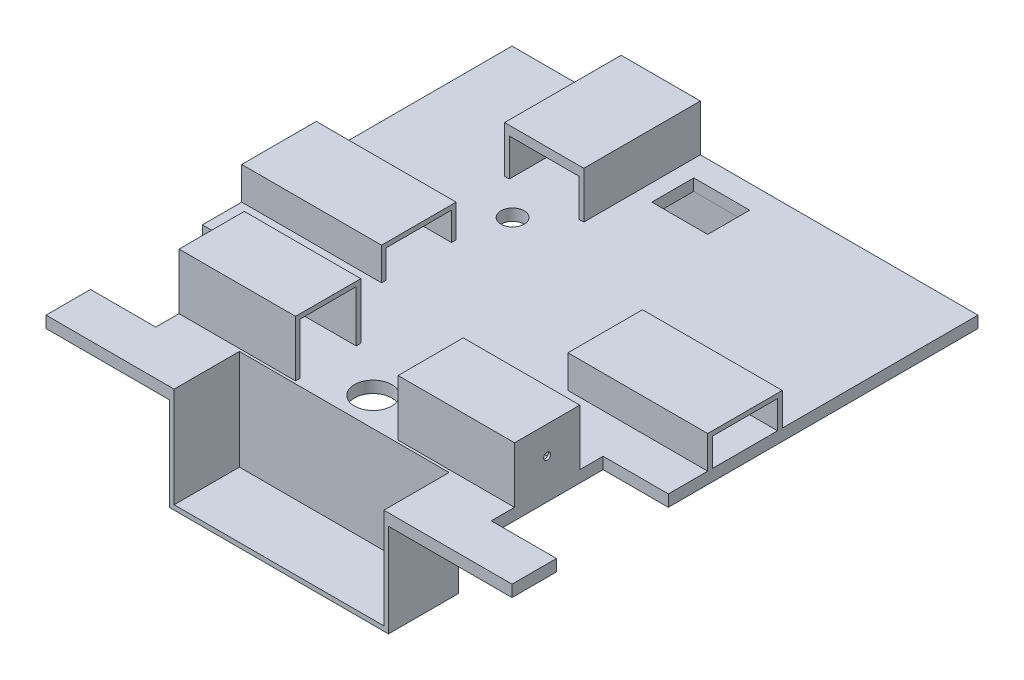
SolidWorks part; units mm, degrees
ref_plane "Front Plane" through (0, 0, 0) normal (0, 0, 1) x (1, 0, 0)
ref_plane "Top Plane" through (0, 0, 0) normal (0, 1, 0) x (1, 0, 0)
ref_plane "Right Plane" through (0, 0, 0) normal (1, 0, 0) x (0, 0, -1)
sketch "Sketch1" plane through (0, 0, 0) normal (0, 1, 0) x (1, 0, 0)
  line L0 (-50, -50) -> (-50, 50)
  line L1 (-50, -50) -> (50, -50)
  line L2 (-50, 50) -> (50, 50)
  line L3 (50, -50) -> (50, 50)
  line L4 (50, -16.4531) -> (36, -16.4531)
  line L5 (36, -16.4531) -> (36, -40.4531)
  line L6 (36, -40.4531) -> (50, -40.4531)
  line L7 (-36, -40.4531) -> (-50, -40.4531)
  line L8 (-36, -16.4531) -> (-36, -40.4531)
  line L9 (-50, -16.4531) -> (-36, -16.4531)
  line L10 (-6, 45) -> (6, 45)
  line L11 (-6, 45) -> (-6, 36)
  line L12 (6, 45) -> (6, 36)
  line L13 (-6, 36) -> (6, 36)
  dimension "D1" = 14
  dimension "D2" = 24
  dimension "D3" = 9
  dimension "D4" = 12
extrude "Boss-Extrude1" add sketch "Sketch1" along normal blind 2.5 contours L0 L9 L8 L7 L1 L3 L6 L5 L4 L2 L13 L11 L10 L12
sketch "Sketch2" plane through (0, 2.5, 0) normal (0, 1, 0) x (1, 0, 0)
  line L0 (-26.5835, 50) -> (-9.5835, 50)
  line L1 (-26.5835, 50) -> (-26.5835, 25)
  line L2 (-9.5835, 50) -> (-9.5835, 25)
  line L3 (-26.5835, 25) -> (-9.5835, 25)
  line L4 (-50, 50) -> (50, 50) construction
  dimension "D1" = 17
  dimension "D2" = 25
extrude "Boss-Extrude2" add sketch "Sketch2" along normal blind 10
sketch "Sketch4" plane through (0, 0, -25) normal (0, 0, 1) x (1, 0, 0)
  line L0 (-25.5835, 2.5) -> (-10.5835, 2.5)
  line L1 (-25.5835, 2.5) -> (-25.5835, 10.5)
  line L2 (-10.5835, 2.5) -> (-10.5835, 10.5)
  line L3 (-25.5835, 10.5) -> (-10.5835, 10.5)
  line L5 (-26.5835, 2.5) -> (-9.5835, 2.5) construction
  line L6 (-26.5835, 12.5) -> (-26.5835, 2.5) construction
  line L7 (-9.5835, 12.5) -> (-9.5835, 2.5) construction
  line L8 (-26.5835, 12.5) -> (-9.5835, 12.5) construction
  dimension "D1" = 1
  dimension "D2" = 1
  dimension "D3" = 2
extrude "Cut-Extrude1" cut sketch "Sketch4" against normal blind 42
sketch "Sketch5" plane through (0, 2.5, 0) normal (0, 1, 0) x (1, 0, 0)
  line L0 (-9.5835, 25) -> (-9.5835, 50) construction
  circle A0 centre (-18.0835, 18.2093) radius 2.5
  dimension "D2" = 5
  dimension "D1" = 8.5
sketch "Sketch7" plane through (-36, 0, 0) normal (-1, 0, 0) x (0, 0, 1)
  line L0 (21.4531, 2.5) -> (21.4531, 14.5)
  line L1 (21.4531, 2.5) -> (35.4531, 2.5)
  line L2 (21.4531, 14.5) -> (35.4531, 14.5)
  line L3 (35.4531, 2.5) -> (35.4531, 14.5)
  line L4 (16.4531, 2.5) -> (40.4531, 2.5) construction
  line L5 (16.4531, 2.5) -> (16.4531, 0) construction
  dimension "D1" = 14
  dimension "D2" = 5
  dimension "D3" = 12
extrude "Boss-Extrude3" add sketch "Sketch7" against normal blind 72
sketch "Sketch8" plane through (-36, 0, 0) normal (-1, 0, 0) x (0, 0, 1)
  line L0 (21.4531, 14.5) -> (21.4531, 2.5) construction
  line L1 (35.4531, 14.5) -> (21.4531, 14.5) construction
  circle A0 centre (28.4531, 8.5) radius 0.75
  dimension "D1" = 1.5
  dimension "D2" = 7
  dimension "D3" = 6
extrude "Cut-Extrude2" cut sketch "Sketch8" against normal blind 72
sketch "Sketch9" plane through (0, 0, 35.4531) normal (0, 0, 1) x (1, 0, 0)
  line L0 (-11, 14.5) -> (-11, 2.5)
  line L1 (-11, 14.5) -> (11, 14.5)
  line L2 (-11, 2.5) -> (11, 2.5)
  line L3 (11, 14.5) -> (11, 2.5)
  line L4 (36, 14.5) -> (-36, 14.5) construction
  line L6 (36, 2.5) -> (36, 14.5) construction
  line L7 (36, 2.5) -> (-36, 2.5) construction
  line L8 (-36, 2.5) -> (-36, 14.5) construction
  dimension "D1" = 25
  dimension "D2" = 25
extrude "Cut-Extrude3" cut sketch "Sketch9" against normal blind 37
extrude "Cut-Extrude6" cut sketch "Sketch5" against normal blind 23.5 contours A0
sketch "Sketch12" plane through (0, 0, 0) normal (0, -1, 0) x (1, 0, 0)
  line L0 (-23.5, 50) -> (23.5, 50)
  line L1 (-23.5, 50) -> (-23.5, 35)
  line L2 (23.5, 50) -> (23.5, 35)
  line L3 (-23.5, 35) -> (23.5, 35)
  line L4 (-50, 50) -> (50, 50) construction
  line L5 (50, 50) -> (50, 40.4531) construction
  dimension "D1" = 47
  dimension "D2" = 26.5
  dimension "D3" = 15
extrude "Boss-Extrude4" add sketch "Sketch12" along normal blind 20
sketch "Sketch13" plane through (0, 0, 50) normal (0, 0, 1) x (1, 0, 0)
  line L0 (-22.5, -19) -> (-22.5, 2.5)
  line L1 (-22.5, -19) -> (22.5, -19)
  line L2 (-22.5, 2.5) -> (22.5, 2.5)
  line L3 (22.5, -19) -> (22.5, 2.5)
  line L6 (23.5, -20) -> (23.5, 0) construction
  line L7 (-50, 2.5) -> (50, 2.5) construction
  line L10 (23.5, -20) -> (-23.5, -20) construction
  dimension "D1" = 45
  dimension "D2" = 1
  dimension "D3" = 1
extrude "Cut-Extrude7" cut sketch "Sketch13" against normal blind 14
sketch "Sketch14" plane through (0, 0, 0) normal (0, -1, 0) x (1, 0, 0)
  line L0 (-23.5, -50) -> (23.5, -50)
  line L1 (-23.5, -50) -> (-23.5, -45.0836)
  line L2 (23.5, -50) -> (23.5, -45.0836)
  line L3 (-23.5, -45.0836) -> (23.5, -45.0836)
  line L4 (-50, -50) -> (50, -50) construction
  line L5 (-23.5, 50) -> (-23.5, 35) construction
  line L6 (23.5, 35) -> (23.5, 50) construction
extrude "Boss-Extrude5" add sketch "Sketch14" along normal blind 20
sketch "Sketch15" plane through (0, -20, 0) normal (0, -1, 0) x (1, 0, 0)
  line L0 (-22.5, -50) -> (-22.5, -46.0836)
  line L1 (-22.5, -50) -> (22.5, -50)
  line L2 (-22.5, -46.0836) -> (22.5, -46.0836)
  line L3 (22.5, -50) -> (22.5, -46.0836)
  line L4 (-23.5, -50) -> (23.5, -50) construction
  line L5 (23.5, -45.0836) -> (-23.5, -45.0836) construction
  line L6 (23.5, -50) -> (23.5, -45.0836) construction
  line L7 (-23.5, -45.0836) -> (-23.5, -50) construction
  dimension "D1" = 1
  dimension "D2" = 1
  dimension "D3" = 1
extrude "Cut-Extrude8" cut sketch "Sketch15" against normal blind 20
sketch "Sketch16" plane through (0, 2.5, 0) normal (0, 1, 0) x (1, 0, 0)
  line L0 (-50, 8) -> (-20, 8)
  line L1 (-50, 8) -> (-50, -8)
  line L2 (-20, 8) -> (-20, -8)
  line L3 (-50, -8) -> (-20, -8)
  line L4 (-50, 50) -> (-26.5835, 50) construction
  line L5 (0, 59.0308) -> (0, -50.891) construction
  line L6 (50, -16.4531) -> (50, 50) construction
  line L7 (50, 8) -> (50, -8)
  line L8 (50, -8) -> (20, -8)
  line L9 (20, 8) -> (20, -8)
  line L10 (50, 8) -> (20, 8)
  line L11 (-50, -16.4531) -> (-50, 50) construction
  dimension "D1" = 16
  dimension "D2" = 30
  dimension "D3" = 42
  dimension "D4" = 50
extrude "Boss-Extrude6" add sketch "Sketch16" along normal blind 7
sketch "Sketch17" plane through (-50, 0, 0) normal (-1, 0, 0) x (0, 0, 1)
  line L0 (-7, 2.5) -> (7, 2.5)
  line L1 (-7, 2.5) -> (-7, 8.5)
  line L2 (7, 2.5) -> (7, 8.5)
  line L3 (-7, 8.5) -> (7, 8.5)
  line L4 (-8, 2.5) -> (-50, 2.5) construction
  line L5 (-8, 9.5) -> (8, 9.5) construction
  line L6 (8, 9.5) -> (8, 2.5) construction
  line L7 (-8, 9.5) -> (-8, 2.5) construction
  point P8 (0, 9.5)
  dimension "D1" = 1
  dimension "D2" = 1
  dimension "D3" = 1
extrude "Cut-Extrude9" cut sketch "Sketch17" against normal blind 100
sketch "Sketch19" plane through (-11, 0, 0) normal (1, 0, 0) x (0, 0, -1)
  line L0 (-34.4531, 13.5) -> (-34.4531, 2.5)
  line L1 (-34.4531, 13.5) -> (-22.4531, 13.5)
  line L2 (-34.4531, 2.5) -> (-22.4531, 2.5)
  line L3 (-22.4531, 13.5) -> (-22.4531, 2.5)
  line L4 (-21.4531, 14.5) -> (-35.4531, 14.5) construction
  line L5 (-35.4531, 14.5) -> (-35.4531, 2.5) construction
  line L7 (-21.4531, 2.5) -> (-35.4531, 2.5) construction
  line L8 (-21.4531, 2.5) -> (-21.4531, 14.5) construction
  dimension "D1" = 1
  dimension "D2" = 1
  dimension "D3" = 1
extrude "Cut-Extrude10" cut sketch "Sketch19" against normal blind 24.5 and the other way blind 46.5
sketch "Sketch21" plane through (0, 2.5, 0) normal (0, 1, 0) x (1, 0, 0)
  line L0 (36, -35.4531) -> (36, -21.4531) construction
  circle A0 centre (0, -29.8054) radius 4
  dimension "D1" = 8
  dimension "D2" = 36
extrude "Cut-Extrude11" cut sketch "Sketch21" against normal blind 24.5
